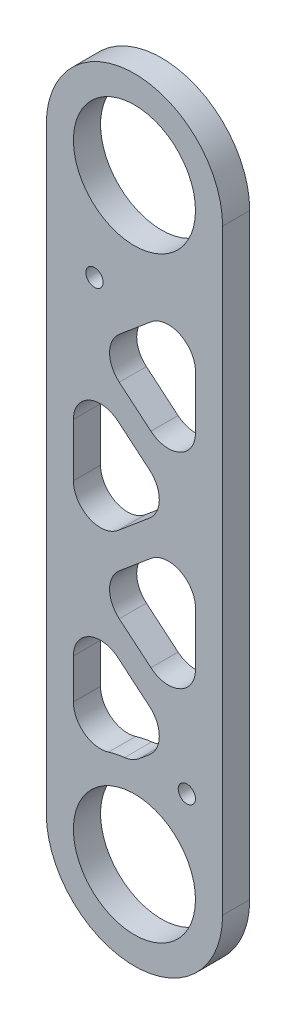
SolidWorks part; units mm, degrees
ref_plane "Front Plane" through (0, 0, 0) normal (0, 0, 1) x (1, 0, 0)
ref_plane "Top Plane" through (0, 0, 0) normal (0, 1, 0) x (1, 0, 0)
ref_plane "Right Plane" through (0, 0, 0) normal (1, 0, 0) x (0, 0, -1)
sketch "Sketch2" plane through (0, 0, 0) normal (0, 0, 1) x (1, 0, 0)
  line L0 (20.6375, 139.7) -> (20.6375, 0)
  line L1 (-20.6375, 139.7) -> (-20.6375, 0)
  circle A0 centre (0, 0) radius 14.2875
  circle A1 centre (0, 139.7) radius 14.2875
  circle A2 centre (0, 139.7) radius 20.6375
  circle A3 centre (0, 0) radius 20.6375
  dimension "D1" = 28.575
  dimension "D2" = 6.35
  dimension "D3" = 139.7
extrude "Boss-Extrude1" add sketch "Sketch2" along normal mid plane 6.35 contours A3 L0 A2 L1 | A2 A1 | A3 A0
sketch "Sketch3" plane through (0, 0, 0) normal (0, 0, 1) x (1, 0, 0)
  line L0 (12.2466, 127.2401) -> (-19.2269, 100.8307)
  line L1 (-19.2269, 100.8307) -> (9.3481, 76.8534)
  line L2 (14.2875, 124.8079) -> (-14.2875, 100.8307) construction
  line L3 (-14.2875, 100.8307) -> (14.2875, 76.8534) construction
  line L4 (-14.2875, 139.7) -> (-14.2875, 0)
  line L5 (14.2875, 0) -> (14.2875, 139.7)
  line L6 (-14.2875, 139.7) -> (-14.2875, 0)
  line L7 (14.2875, 0) -> (14.2875, 139.7)
  line L8 (14.2875, 76.8534) -> (-14.2875, 52.8761) construction
  line L9 (-14.2875, 52.8761) -> (14.2875, 28.8988) construction
  line L10 (14.2875, 28.8988) -> (-14.2875, 4.9216) construction
  line L11 (9.3481, 76.8534) -> (-19.2269, 52.8761)
  line L12 (-19.2269, 52.8761) -> (9.3481, 28.8988)
  line L13 (9.3481, 28.8988) -> (-16.3284, 7.3538)
  line L14 (16.3284, 122.3757) -> (-9.3481, 100.8307)
  line L15 (-9.3481, 100.8307) -> (19.2269, 76.8534)
  line L16 (19.2269, 76.8534) -> (-9.3481, 52.8761)
  line L17 (-9.3481, 52.8761) -> (19.2269, 28.8988)
  line L18 (19.2269, 28.8988) -> (-12.2466, 2.4894)
  circle A1 centre (-9.3481, 114.3244) radius 2.0193
  circle A2 centre (0, 139.7) radius 20.6375
  circle A3 centre (0, 0) radius 20.6375
  arc A4 (-14.2875, 0) -> (14.2875, 0) centre (0, 0) ccw
  arc A5 (14.2875, 139.7) -> (-14.2875, 139.7) centre (0, 139.7) ccw
  arc A6 (-14.2875, 0) -> (14.2875, 0) centre (0, 0) ccw
  arc A7 (14.2875, 139.7) -> (-14.2875, 139.7) centre (0, 139.7) ccw
  circle A8 centre (0, 139.7) radius 14.2875 construction
  circle A9 centre (12.2682, 20.4238) radius 2.0193
  point P19 (-9.3481, 116.0902)
  point P33 (12.2466, 19.6892)
  dimension "D2" = 6.35
  dimension "D3" = 50
  dimension "D7" = 4.0386
  dimension "D8" = 13.4937
  dimension "D5" = 3.175
  dimension "D4" = 80
  dimension "D1" = 6.35
  dimension "D6" = 3.175
extrude "Cut-Extrude1" cut sketch "Sketch3" against normal through all both and the other way through all contours L14 L15 L7 | L11 L1 L6 | L16 L17 L7 | A3 L13 L12 L6 | A1 | A9
fillet "Fillet2" radius 6.35 13 edges at (-14.2875, 57.0208, 0) (-14.2875, 96.686, 0) (9.3481, 76.8534, 0) (14.2875, 80.9981, 0) (-9.3481, 100.8307, 0) (-14.2875, 14.8921, 0) (-14.2875, 48.7314, 0) (9.3481, 28.8988, 0) (-0.5048, 20.6313, 0) (14.2875, 33.0435, 0) (-9.3481, 52.8761, 0) (14.2875, 72.7087, 0) (14.2875, 120.6633, 0)
